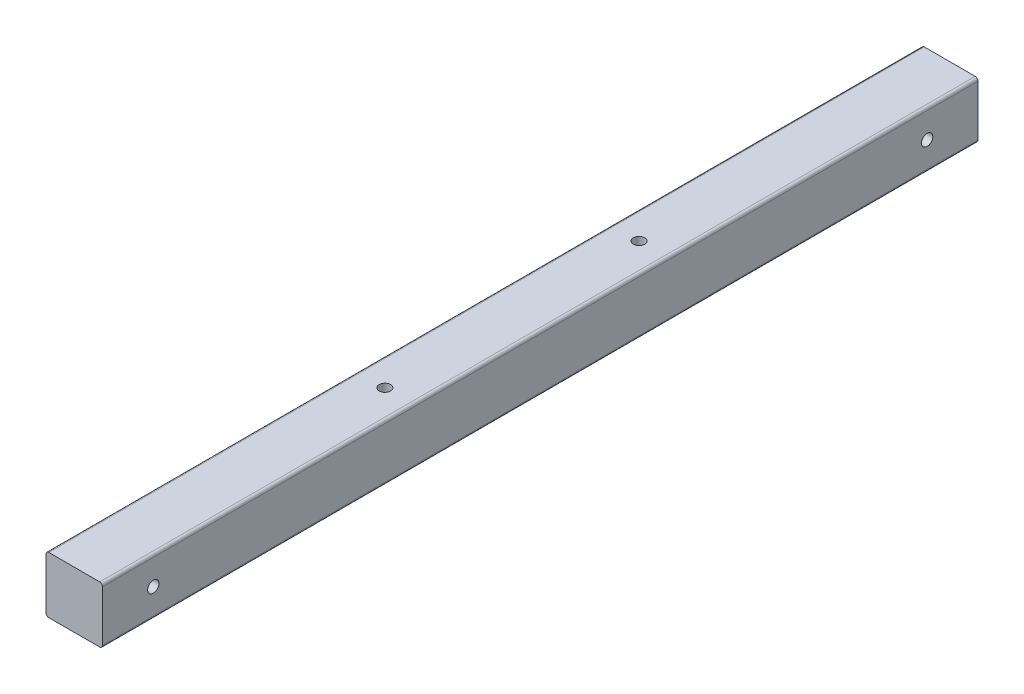
SolidWorks part; units mm, degrees
ref_plane "前视基准面" through (0, 0, 0) normal (0, 0, 1) x (1, 0, 0)
ref_plane "上视基准面" through (0, 0, 0) normal (0, 1, 0) x (1, 0, 0)
ref_plane "右视基准面" through (0, 0, 0) normal (1, 0, 0) x (0, 0, -1)
sketch "草图1" plane through (0, 0, 0) normal (0, 0, 1) x (1, 0, 0)
  line L1 (0, 0) -> (20, 0)
  line L2 (0, 0) -> (0, 20)
  line L3 (0, 20) -> (20, 20)
  line L4 (20, 0) -> (20, 20)
  dimension "D1" = 20
  dimension "D2" = 20
extrude "凸台-拉伸1" add sketch "草图1" along normal blind 310
fillet "圆角1" radius 1 4 edges at (0, 0, 155) (20, 0, 155) (20, 20, 155) (0, 20, 155)
sketch "草图2" plane through (0, 20, 0) normal (0, 1, 0) x (1, 0, 0)
  line L0 (19, -310) -> (1, -310) construction
  line L1 (19, 0) -> (1, 0) construction
  line L2 (20, 0) -> (20, -310) construction
  circle A0 centre (10, -110) radius 2
  circle A1 centre (10, -200) radius 2
  point P10 (0, 0)
  dimension "D4" = 4
  dimension "D1" = 110
  dimension "D2" = 110
  dimension "D3" = 10
extrude "切除-拉伸1" cut sketch "草图2" against normal blind 310
sketch "草图3" plane through (0, 0, 0) normal (-1, 0, 0) x (0, 0, 1)
  line L0 (0, 20) -> (310, 20) construction
  line L1 (0, 19) -> (0, 1) construction
  line L2 (310, 19) -> (310, 1) construction
  circle A0 centre (18, 10) radius 2
  circle A1 centre (292, 10) radius 2
  point P8 (0, 0)
  dimension "D3" = 4
  dimension "D1" = 10
  dimension "D2" = 18
  dimension "D4" = 18
extrude "切除-拉伸2" cut sketch "草图3" against normal blind 310
